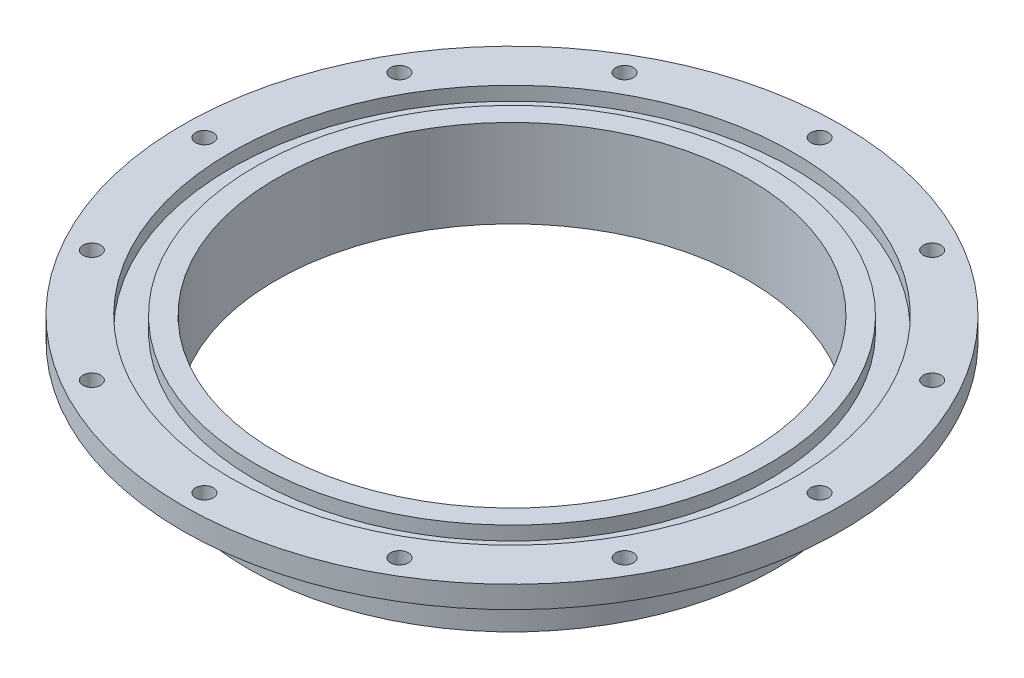
SolidWorks part; units mm, degrees
ref_plane "Front Plane" through (0, 0, 0) normal (0, 0, 1) x (1, 0, 0)
ref_plane "Top Plane" through (0, 0, 0) normal (0, 1, 0) x (1, 0, 0)
ref_plane "Right Plane" through (0, 0, 0) normal (1, 0, 0) x (0, 0, -1)
sketch "Sketch1" plane through (0, 0, 0) normal (0, 1, 0) x (1, 0, 0)
  circle A0 centre (0, 0) radius 76.2
  circle A1 centre (0, 0) radius 68.2625
  dimension "D1" = 152.4
  dimension "D2" = 7.9375
extrude "Inner Cylinder" add sketch "Sketch1" along normal blind 19.05
sketch "Sketch2" plane through (0, 19.05, 0) normal (0, 1, 0) x (1, 0, 0)
  circle A0 centre (0, 0) radius 68.2625
  circle A1 centre (0, 0) radius 68.2625 construction
  circle A2 centre (0, 0) radius 95.25
  dimension "D1" = 190.5
extrude "Flange" add sketch "Sketch2" along normal blind 6.35
sketch "Sketch4" plane through (0, 25.4, 0) normal (0, 1, 0) x (1, 0, 0)
  line L0 (0, 75.8825) -> (0, 81.2165) construction
  circle A3 centre (0, 0) radius 81.407
  circle A4 centre (0, 0) radius 74.295
  point P7 (0, 78.5495)
  dimension "D1" = 148.59
  dimension "D2" = 7.112
  dimension "D3" = 2.667
extrude "Groove" cut sketch "Sketch4" against normal blind 3.9878
sketch "Sketch5" plane through (0, 25.4, 0) normal (0, 1, 0) x (1, 0, 0)
  line L0 (82.55, 0) -> (95.25, 0) construction
  circle A0 centre (0, 0) radius 88.9 construction
  circle A1 centre (0, -88.9) radius 3.175 construction
  circle A3 centre (0, -88.9) radius 2.5527
  circle A6 centre (0, 0) radius 82.55 construction
  circle A7 centre (0, 0) radius 95.25 construction
  point P9 (88.9, 0)
  dimension "D1" = 5.1054
  dimension "D2" = 165.1
  dimension "D3" = 6.35
extrude "Screw Holes" cut sketch "Sketch5" against normal up to surface (6.35 mm away) up to face at (0, 19.05, 76.2)
pattern_circular "CirPattern1" count 12 over 360 about axis through (0, 0, 0) along (0, 1, 0) of "Screw Holes"
sketch "Sketch6" plane through (0, 25.4, 0) normal (0, 1, 0) x (1, 0, 0)
  circle A0 centre (0, 0) radius 82.55
  dimension "D1" = 165.1
ref_plane "Plane1" through (0, 9.525, 0) normal (0, -1, 0) x (-1, 0, 0)
sketch "Sketch7" plane through (0, 9.525, 0) normal (0, -1, 0) x (-1, 0, 0)
  circle A0 centre (0, 0) radius 76.2
  circle A1 centre (0, 0) radius 76.2 construction
  circle A2 centre (0, 0) radius 71.8566
  dimension "D1" = 4.3434
extrude "Cut-Extrude1" cut sketch "Sketch7" against normal blind 3.6068 and the other way blind 3.6068
